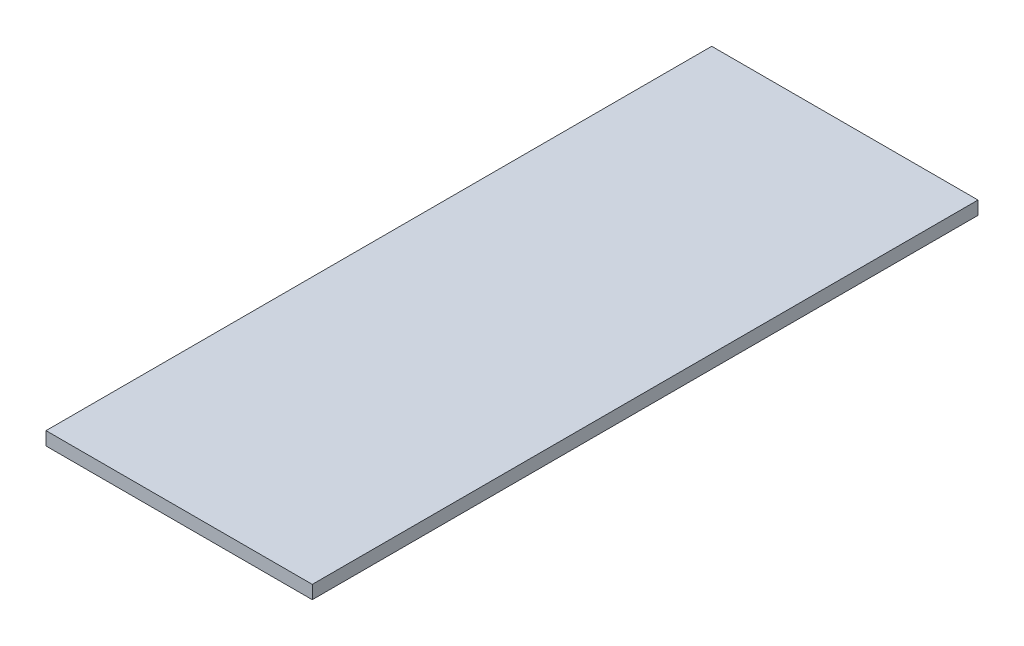
SolidWorks part; units mm, degrees
ref_plane "Front Plane" through (0, 0, 0) normal (0, 0, 1) x (1, 0, 0)
ref_plane "Top Plane" through (0, 0, 0) normal (0, 1, 0) x (1, 0, 0)
ref_plane "Right Plane" through (0, 0, 0) normal (1, 0, 0) x (0, 0, -1)
sketch "Sketch1" plane through (0, 0, 0) normal (0, 1, 0) x (1, 0, 0)
  line L1 (-60, -150) -> (60, -150)
  line L2 (-60, -150) -> (-60, 150)
  line L3 (-60, 150) -> (60, 150)
  line L4 (60, -150) -> (60, 150)
extrude "Shelf_blank_no_mounting_design" add sketch "Sketch1" along normal blind 6 from offset 0 separate body
